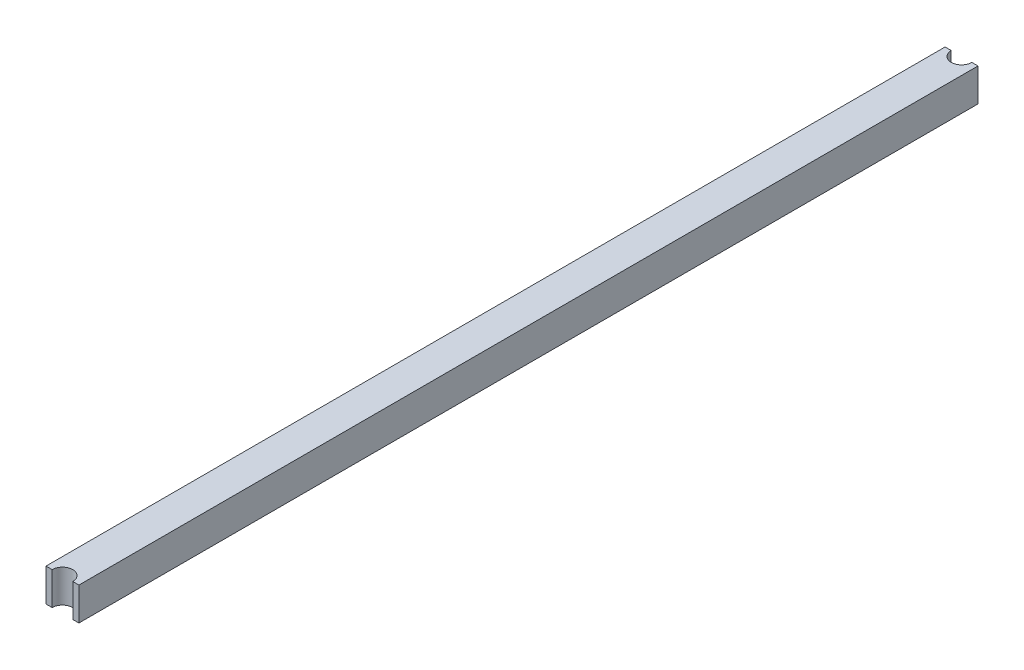
SolidWorks part; units mm, degrees
material "Plain Carbon Steel"
ref_plane "Front Plane" through (0, 0, 0) normal (0, 0, 1) x (1, 0, 0)
ref_plane "Top Plane" through (0, 0, 0) normal (0, 1, 0) x (1, 0, 0)
ref_plane "Right Plane" through (0, 0, 0) normal (1, 0, 0) x (0, 0, -1)
sketch "Sketch1" plane through (0, 0, 0) normal (0, 0, 1) x (1, 0, 0)
  line L1 (0, 0) -> (-31.1, 0)
  line L2 (0, 0) -> (0, 31.1)
  line L3 (0, 31.1) -> (-31.1, 31.1)
  line L4 (-31.1, 0) -> (-31.1, 31.1)
extrude "Boss-Extrude1" add sketch "Sketch1" along normal blind 850
sketch "Sketch2" plane through (0, 31.1, 0) normal (0, 1, 0) x (1, 0, 0)
  line L0 (0, 0) -> (-31.1, 0) construction
  line L1 (0, -850) -> (-31.1, -850) construction
  circle A0 centre (-15.55, 0) radius 9.755
  circle A1 centre (-15.55, -850) radius 9.755
extrude "Cut-Extrude1" cut sketch "Sketch2" against normal blind 31.1
